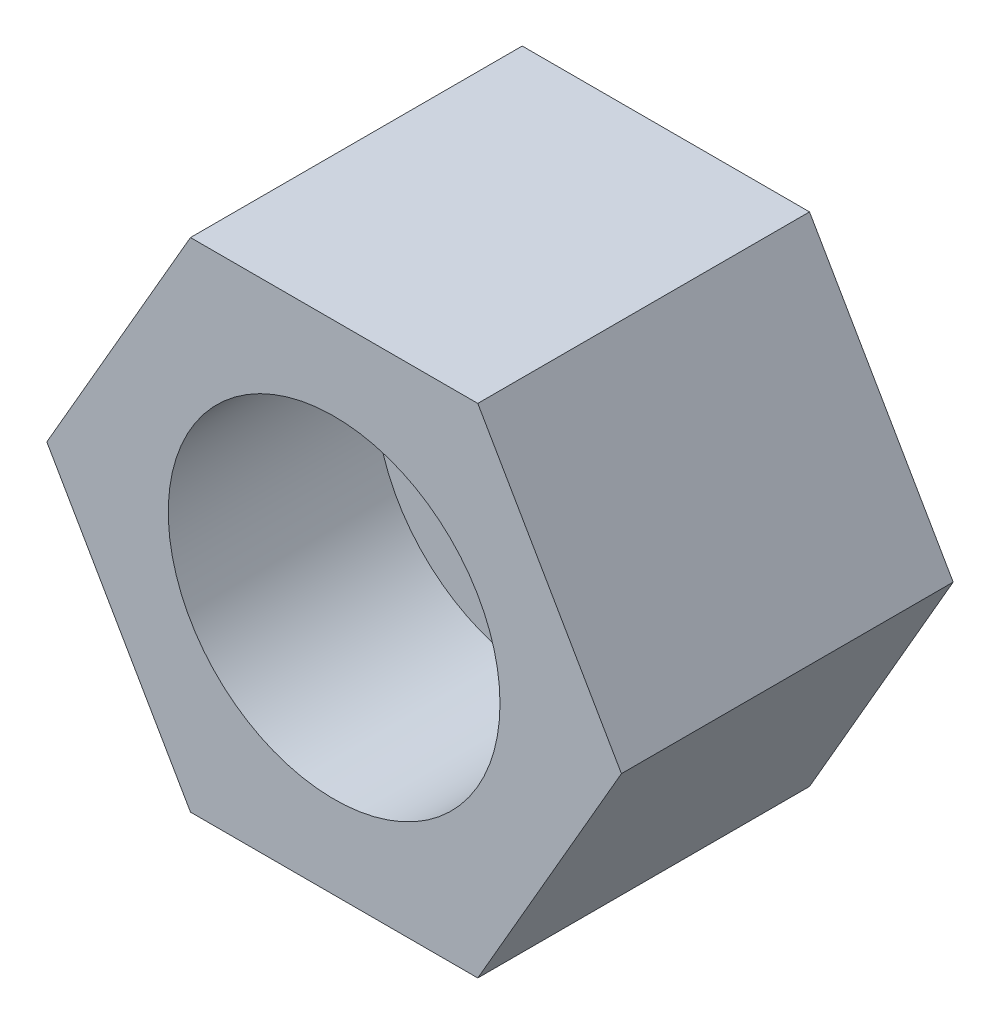
SolidWorks part; units mm, degrees
material "Brass"
ref_plane "Front Plane" through (0, 0, 0) normal (0, 0, 1) x (1, 0, 0)
ref_plane "Top Plane" through (0, 0, 0) normal (0, 1, 0) x (1, 0, 0)
ref_plane "Right Plane" through (0, 0, 0) normal (1, 0, 0) x (0, 0, -1)
sketch "Sketch1" plane through (0, 0, 0) normal (0, 0, 1) x (1, 0, 0)
  line L1 (6.9282, 0) -> (3.4641, 6)
  line L2 (3.4641, 6) -> (-3.4641, 6)
  line L3 (-3.4641, 6) -> (-6.9282, 0)
  line L4 (-6.9282, 0) -> (-3.4641, -6)
  line L5 (-3.4641, -6) -> (3.4641, -6)
  line L6 (3.4641, -6) -> (6.9282, 0)
  circle A0 centre (0, 0) radius 6 construction
  circle A1 centre (0, 0) radius 2.5
  dimension "D2" = 5
  dimension "D1" = 12
extrude "Boss-Extrude1" add sketch "Sketch1" along normal mid plane 8
sketch "Sketch2" plane through (0, 0, 4) normal (0, 0, 1) x (1, 0, 0)
  circle A0 centre (0, 0) radius 4
  dimension "D1" = 8
extrude "Cut-Extrude1" cut sketch "Sketch2" against normal blind 5
cosmetic thread "Cosmetic Thread1" parameters "D2"=10
